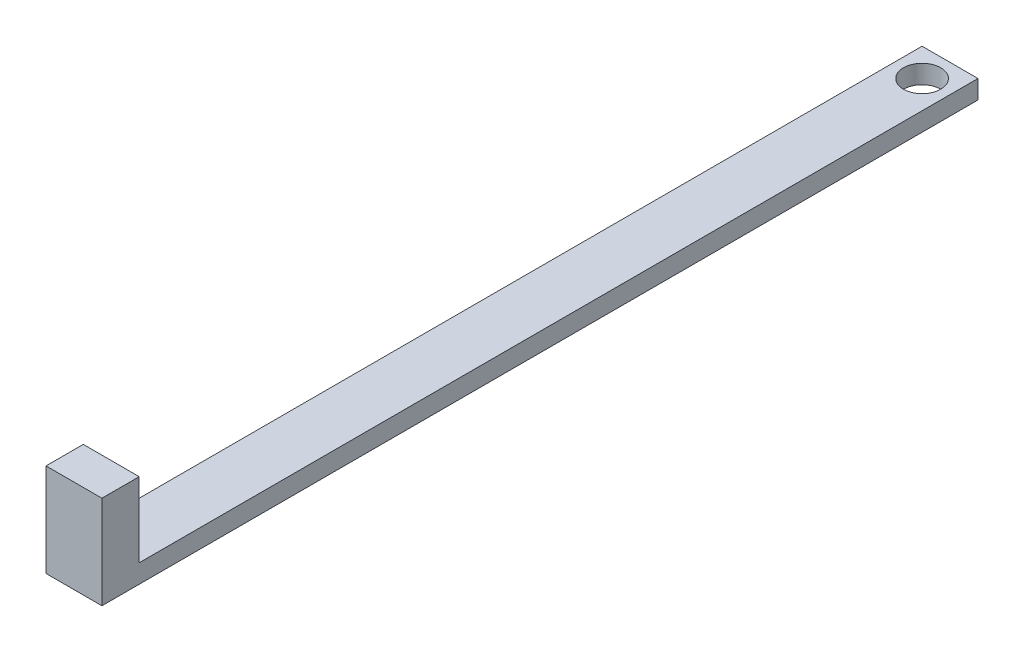
SolidWorks part; units mm, degrees
ref_plane "Front Plane" through (0, 0, 0) normal (0, 0, 1) x (1, 0, 0)
ref_plane "Top Plane" through (0, 0, 0) normal (0, 1, 0) x (1, 0, 0)
ref_plane "Right Plane" through (0, 0, 0) normal (1, 0, 0) x (0, 0, -1)
sketch "Sketch1" plane through (0, 0, 0) normal (1, 0, 0) x (0, 0, -1)
  line L0 (0, 40) -> (0, 0)
  line L1 (0, 0) -> (450, 0)
  line L2 (450, 0) -> (450, -10)
  line L3 (450, -10) -> (-20, -10)
  line L4 (-20, -10) -> (-20, 40)
  line L5 (-20, 40) -> (0, 40)
  dimension "D1" = 10
  dimension "D2" = 450
  dimension "D3" = 470
  dimension "D4" = 50
extrude "Boss-Extrude1" add sketch "Sketch1" along normal blind 30
sketch "Sketch2" plane through (0, 0, 0) normal (0, 1, 0) x (1, 0, 0)
  line L0 (30, 450) -> (0, 450) construction
  line L1 (30, 450) -> (30, 0) construction
  circle A0 centre (15, 435) radius 10
  dimension "D1" = 20
  dimension "D2" = 15
  dimension "D3" = 15
extrude "Cut-Extrude1" cut sketch "Sketch2" against normal blind 10
